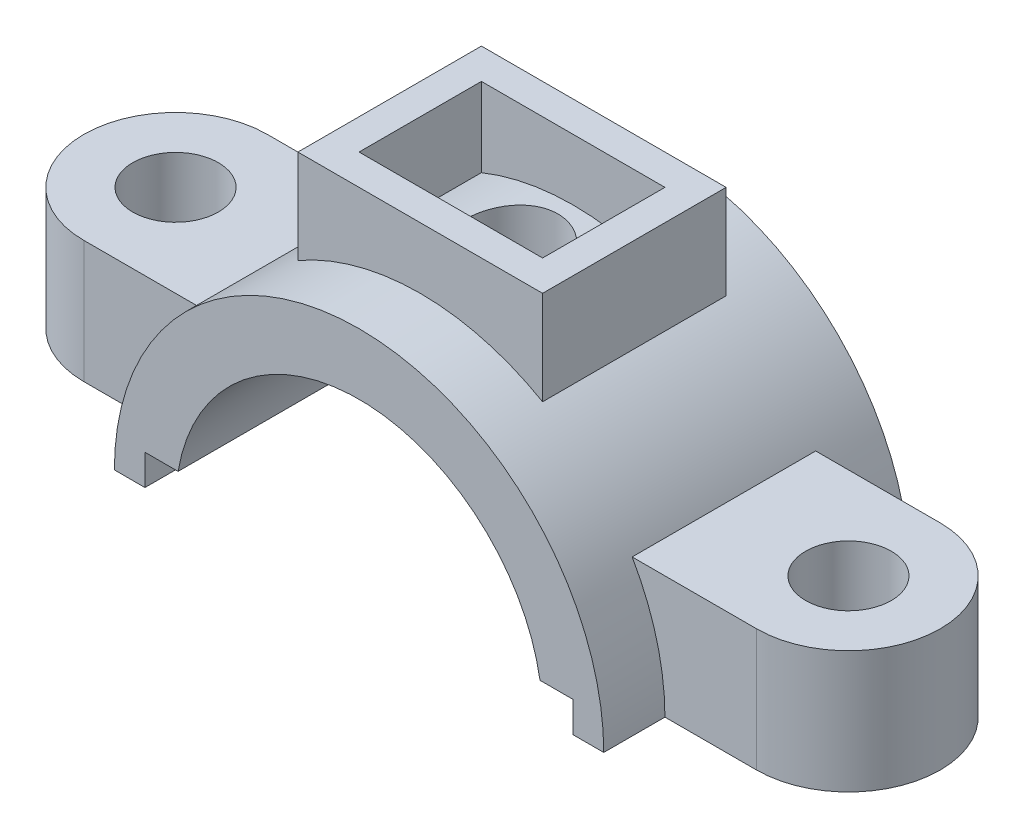
SolidWorks part; units mm, degrees
ref_plane "Front Plane" through (0, 0, 0) normal (0, 0, 1) x (1, 0, 0)
ref_plane "Top Plane" through (0, 0, 0) normal (0, 1, 0) x (1, 0, 0)
ref_plane "Right Plane" through (0, 0, 0) normal (1, 0, 0) x (0, 0, -1)
sketch "Sketch1" plane through (0, 0, 0) normal (0, 1, 0) x (1, 0, 0)
  line L1 (-55, 15) -> (55, 15)
  line L3 (-55, -15) -> (55, -15)
  arc A0 (-55, 15) -> (-55, -15) centre (-55, 0) ccw
  arc A1 (55, -15) -> (55, 15) centre (55, 0) ccw
  circle A2 centre (-55, 0) radius 7
  circle A3 centre (55, 0) radius 7
  point P0 (0, 0)
  dimension "D1" = 14
  dimension "D2" = 14
  dimension "D3" = 55
  dimension "D4" = 15
  dimension "D5" = 55
extrude "Boss-Extrude1" add sketch "Sketch1" against normal blind 20
sketch "Sketch2" plane through (0, 0, 15) normal (0, 0, 1) x (1, 0, 0)
  line L0 (-55, -20) -> (55, -20) construction
  line L1 (-40, -20) -> (-35, -20)
  line L2 (-35, -15) -> (-29.5804, -15)
  line L3 (-55, -20) -> (-55, 0) construction
  line L4 (-55, 0) -> (55, 0) construction
  line L10 (-35, -15) -> (-35, -20)
  line L11 (-40, -15) -> (46.815, -15) construction
  line L12 (35, -15) -> (35, -20)
  line L14 (29.5804, -15) -> (35, -15)
  line L16 (35, -20) -> (40, -20)
  line L17 (-40, -20) -> (46.815, -20) construction
  arc A1 (40, -20) -> (-40, -20) centre (0, -20) ccw
  arc A2 (29.5804, -15) -> (-29.5804, -15) centre (0, -20) ccw
  point P1 (97.0533, 12.9536)
  point P4 (-84.0278, 12.9536)
  point P9 (-251.5495, 57.8051)
  point P10 (181.9447, -34.7297)
  point P20 (181.9447, -34.7297)
  point P24 (-251.5495, 57.8051)
  dimension "D1" = 30
  dimension "D2" = 80
  dimension "D4" = 20
  dimension "D5" = 90
  dimension "D6" = 110
  dimension "D7" = 110
  dimension "D8" = 20
  dimension "D3" = 5
extrude "Boss-Extrude2" add sketch "Sketch2" along normal blind 10 and the other way blind 40 contours A2 L2 L10 L1 A1 L16 L12 L14
sketch "Sketch3" plane through (0, 0, 15) normal (0, 0, 1) x (1, 0, 0)
  line L0 (-35, -20) -> (-35, -15)
  line L1 (-35, -15) -> (-29.5804, -15)
  line L2 (-35, -20) -> (35, -20)
  line L3 (35, -20) -> (35, -15)
  line L4 (35, -15) -> (29.5804, -15)
  arc A0 (29.5804, -15) -> (-29.5804, -15) centre (0, -20) ccw
extrude "Cut-Extrude1" cut sketch "Sketch3" against normal blind 72
sketch "Sketch7" plane through (0, 0, 25) normal (0, 0, 1) x (1, 0, 0)
  line L0 (-55, -20) -> (-40, -20) construction
  line L1 (-20, 30) -> (20, 30)
  line L2 (-20, 30) -> (-20, 14.641)
  line L4 (20, 30) -> (20, 14.641)
  arc A0 (20, 14.641) -> (-20, 14.641) centre (0, -20) ccw
  point P3 (0, 20)
  dimension "D2" = 40
  dimension "D1" = 50
  dimension "D3" = 40
  dimension "D4" = 20
extrude "Boss-Extrude5" add sketch "Sketch7" against normal blind 40 contours L1 L4 A0 L2
sketch "Sketch10" plane through (0, 0, 25) normal (0, 0, 1) x (1, 0, 0)
  line L0 (-20, 14.641) -> (-20, 30)
  line L1 (-20, 30) -> (20, 30)
  line L2 (20, 30) -> (20, 14.641)
  arc A0 (20, 14.641) -> (-20, 14.641) centre (0, -20) ccw
extrude "Cut-Extrude3" cut sketch "Sketch10" against normal blind 10
sketch "Sketch11" plane through (0, 30, 0) normal (0, 1, 0) x (1, 0, 0)
  line L4 (15, -10) -> (-15, -10)
  line L5 (-15, -10) -> (-15, 10)
  line L6 (-15, 10) -> (15, 10)
  line L7 (15, 10) -> (15, -10)
  line L8 (20, 15) -> (20, -15) construction
  line L9 (20, -15) -> (-20, -15) construction
  dimension "D1" = 5
  dimension "D2" = 35
  dimension "D3" = 5
  dimension "D4" = 25
  dimension "D5" = 30
extrude "Cut-Extrude5" cut sketch "Sketch11" against normal up to surface (12.919 mm away) contours L7 L4 L5 L6
sketch "Sketch12" plane through (0, 30, 0) normal (0, 1, 0) x (1, 0, 0)
  circle A0 centre (0, 0) radius 7.5
  dimension "D1" = 15
extrude "Cut-Extrude6" cut sketch "Sketch12" against normal blind 70
